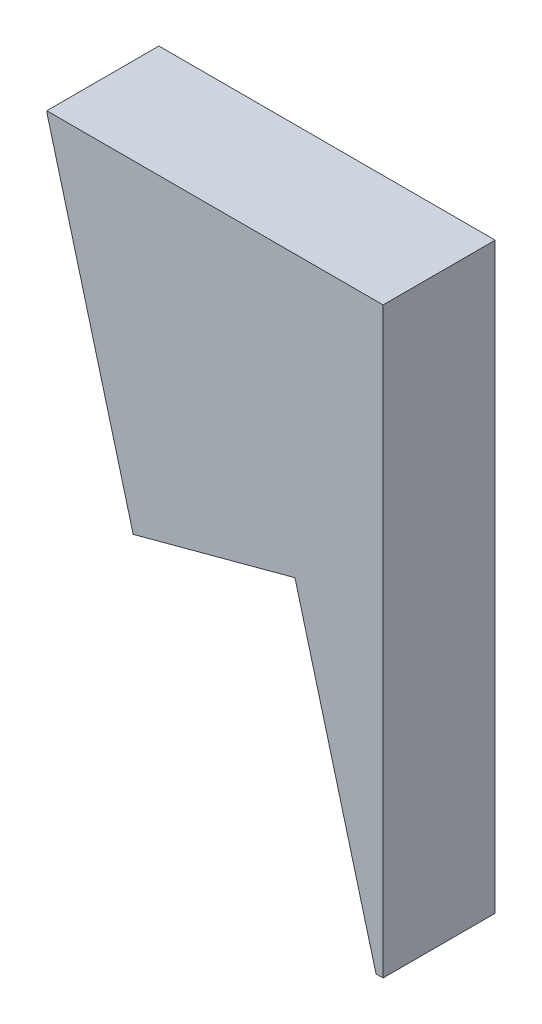
SolidWorks part; units mm, degrees
ref_plane "Plan de face" through (0, 0, 0) normal (0, 0, 1) x (1, 0, 0)
ref_plane "Plan de dessus" through (0, 0, 0) normal (0, 1, 0) x (1, 0, 0)
ref_plane "Plan de droite" through (0, 0, 0) normal (1, 0, 0) x (0, 0, -1)
sketch "Model" plane through (0, 0, 0) normal (0, 0, 1) x (1, 0, 0)
  line L20 (401.0381, -135.9304) -> (415.4667, -132.0642)
  line L21 (415.4667, -132.0642) -> (422.6989, -159.0553)
  line L22 (422.6989, -159.0553) -> (423.332, -159.0553)
  line L23 (423.332, -159.0553) -> (423.332, -107.0553)
  line L24 (423.332, -107.0553) -> (393.332, -107.0553)
  line L25 (393.332, -107.0553) -> (393.332, -107.1709)
  line L26 (393.332, -107.1709) -> (401.0381, -135.9304)
extrude "Boss.-Extru.1" add sketch "Model" along normal blind 10
